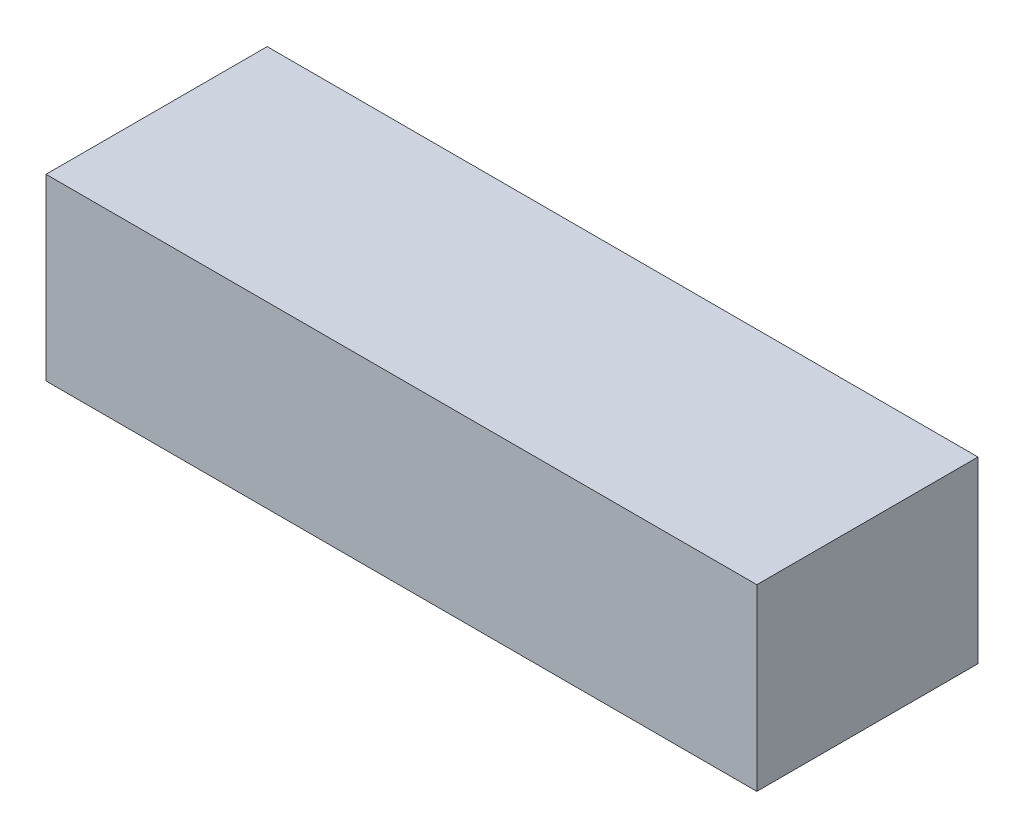
SolidWorks part; units mm, degrees
material "Rubber"
ref_plane "Front Plane" through (0, 0, 0) normal (0, 0, 1) x (1, 0, 0)
ref_plane "Top Plane" through (0, 0, 0) normal (0, 1, 0) x (1, 0, 0)
ref_plane "Right Plane" through (0, 0, 0) normal (1, 0, 0) x (0, 0, -1)
sketch "Sketch1" plane through (0, 0, 0) normal (0, 1, 0) x (1, 0, 0)
  line L1 (-67.5, 21) -> (67.5, 21)
  line L2 (-67.5, 21) -> (-67.5, -21)
  line L3 (-67.5, -21) -> (67.5, -21)
  line L4 (67.5, 21) -> (67.5, -21)
  line L5 (-67.5, 21) -> (67.5, -21) construction
  line L6 (-67.5, -21) -> (67.5, 21) construction
  point P0 (0, 0)
  dimension "D1" = 135
  dimension "D2" = 42
extrude "Boss-Extrude1" add sketch "Sketch1" along normal blind 34
